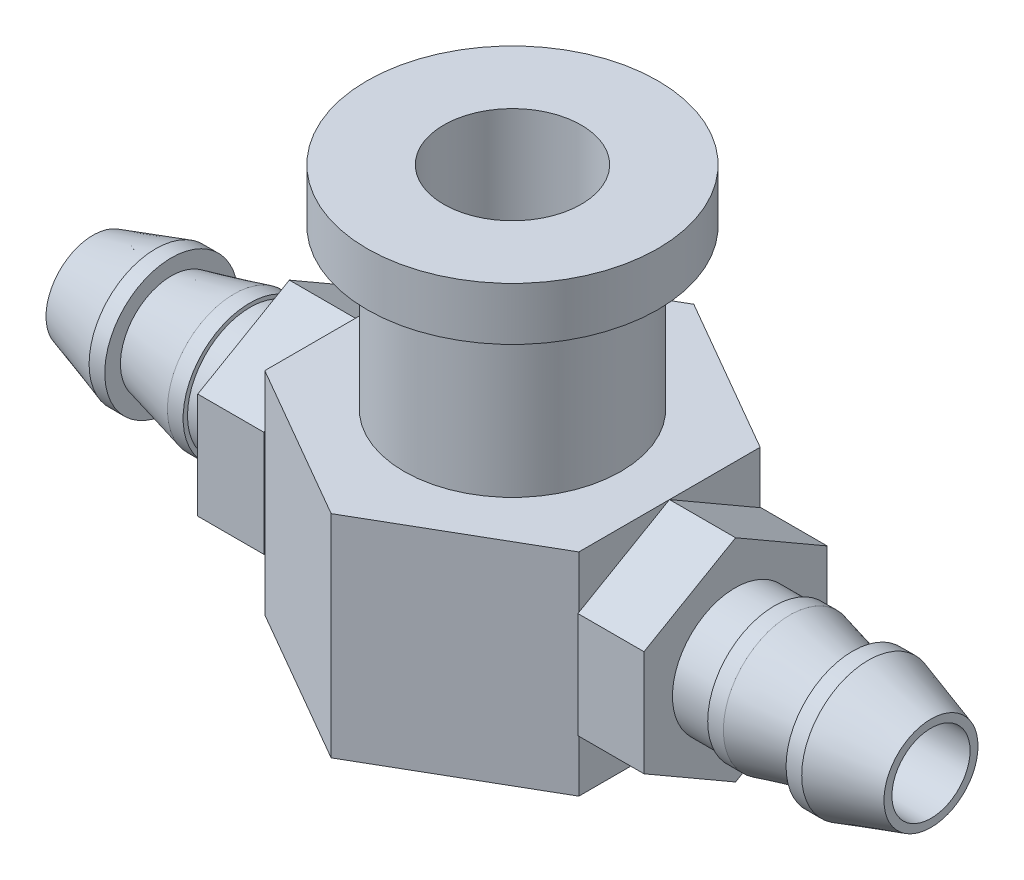
SolidWorks part; units mm, degrees
ref_plane "Front Plane" through (0, 0, 0) normal (0, 0, 1) x (1, 0, 0)
ref_plane "Top Plane" through (0, 0, 0) normal (0, 1, 0) x (1, 0, 0)
ref_plane "Right Plane" through (0, 0, 0) normal (1, 0, 0) x (0, 0, -1)
sketch "Sketch1" plane through (0, 0, 0) normal (0, 1, 0) x (1, 0, 0)
  circle A0 centre (0, 0) radius 4.1
  circle A1 centre (0, 0) radius 5.5
extrude "Boss-Extrude1" add sketch "Sketch1" along normal blind 2
sketch "Sketch2" plane through (0, 2, 0) normal (0, 1, 0) x (1, 0, 0)
  circle A0 centre (0, 0) radius 4.1
extrude "Boss-Extrude2" add sketch "Sketch2" against normal blind 8 separate body
sketch "Sketch4" plane through (0, 2, 0) normal (0, 1, 0) x (1, 0, 0)
  circle A0 centre (0, 0) radius 2.6
extrude "Boss-Extrude3" add sketch "Sketch4" against normal blind 22
sketch "Sketch5" plane through (0, -6, 0) normal (0, -1, 0) x (1, 0, 0)
  line L0 (0, 4.1) -> (0, 8.1972) construction
  line L1 (5.9385, -3.4286) -> (5.9385, 3.4286)
  line L2 (5.9385, 3.4286) -> (0, 6.8571)
  line L3 (0, 6.8571) -> (-5.9385, 3.4286)
  line L4 (-5.9385, 3.4286) -> (-5.9385, -3.4286)
  line L5 (-5.9385, -3.4286) -> (0, -6.8571)
  line L6 (0, -6.8571) -> (5.9385, -3.4286)
  line L7 (0, 4.1) -> (0, -9.45) construction
  circle A0 centre (0, 0) radius 5.9385 construction
  circle A1 centre (0, 0) radius 4.1 construction
  circle A2 centre (0, 0) radius 4.1 construction
  dimension "D1" = 13.7143
extrude "Boss-Extrude4" add sketch "Sketch5" along normal blind 8
sketch "Sketch6" plane through (5.9385, 0, 0) normal (1, 0, 0) x (0, 0, -1)
  line L0 (0, -6) -> (0, -14) construction
  line L1 (3.4286, -6) -> (-3.4286, -6) construction
  line L2 (3.4286, -14) -> (-3.4286, -14) construction
  line L4 (0, -14) -> (3.4641, -12)
  line L5 (3.4641, -12) -> (3.4641, -8)
  line L6 (3.4641, -8) -> (0, -6)
  line L7 (0, -6) -> (-3.4641, -8)
  line L8 (-3.4641, -8) -> (-3.4641, -12)
  line L9 (-3.4641, -12) -> (0, -14)
  circle A0 centre (0, -10) radius 3.4641 construction
extrude "Boss-Extrude5" add sketch "Sketch6" along normal blind 2.5
sketch "Sketch7" plane through (-5.9385, 0, 0) normal (-1, 0, 0) x (0, 0, 1)
  line L0 (0, -6) -> (0, -14) construction
  line L1 (3.4286, -6) -> (-3.4286, -6) construction
  line L2 (-2.6, -14) -> (2.6, -14) construction
  line L4 (0, -14) -> (3.4641, -12)
  line L5 (3.4641, -12) -> (3.4641, -8)
  line L6 (3.4641, -8) -> (0, -6)
  line L7 (0, -6) -> (-3.4641, -8)
  line L8 (-3.4641, -8) -> (-3.4641, -12)
  line L9 (-3.4641, -12) -> (0, -14)
  circle A0 centre (0, -10) radius 3.4641 construction
extrude "Boss-Extrude6" add sketch "Sketch7" along normal blind 2.5
sketch "Sketch8" plane through (0, 2, 0) normal (0, 1, 0) x (1, 0, 0)
  circle A0 centre (0, 0) radius 2.6
extrude "Cut-Extrude1" cut sketch "Sketch8" against normal up to surface (16 mm away) up to face at (0, -14, -2.6)
sketch "Sketch9" plane through (8.4385, 0, 0) normal (1, 0, 0) x (0, 0, -1)
  line L0 (-3.4641, -10) -> (3.4286, -10) construction
  line L1 (-3.4641, -8) -> (-3.4641, -12) construction
  line L2 (3.4286, -12.0205) -> (3.4286, -7.9795) construction
  circle A0 centre (-0.0178, -10) radius 2.3704
  dimension "D1" = 4.7407
extrude "Boss-Extrude7" add sketch "Sketch9" along normal blind 1.4815
sketch "Sketch10" plane through (-8.4385, 0, 0) normal (-1, 0, 0) x (0, 0, 1)
  line L0 (0, -6) -> (0, -14) construction
  circle A0 centre (0, -10) radius 2.3704
  dimension "D1" = 4.7407
extrude "Boss-Extrude8" add sketch "Sketch10" along normal blind 1.4815
sketch "Sketch11" plane through (9.9199, 0, 0) normal (1, 0, 0) x (0, 0, -1)
  circle A0 centre (-0.0178, -10) radius 2.5185
  dimension "D1" = 5.037
extrude "Boss-Extrude9" add sketch "Sketch11" along normal blind 0.5926
ref_plane "Plane1" through (12.8829, 0, 0) normal (1, 0, 0) x (0, 0, -1)
sketch "Sketch12" plane through (12.8829, 0, 0) normal (1, 0, 0) x (0, 0, -1)
  circle A0 centre (-0.0178, -10) radius 1.9259
  dimension "D1" = 3.8519
sketch "Sketch13" plane through (10.5125, 0, 0) normal (1, 0, 0) x (0, 0, -1)
  circle A0 centre (-0.0178, -10) radius 2.5185
loft "Loft1" add profiles "Sketch13", "Sketch12"
sketch "Sketch14" plane through (12.8829, 0, 0) normal (1, 0, 0) x (0, 0, -1)
  circle A0 centre (-0.0178, -10) radius 2.5185
extrude "Boss-Extrude10" add sketch "Sketch14" along normal blind 0.5926
ref_plane "Plane2" through (15.8459, 0, 0) normal (1, 0, 0) x (0, 0, -1)
sketch "Sketch15" plane through (15.8459, 0, 0) normal (1, 0, 0) x (0, 0, -1)
  circle A0 centre (-0.0178, -10) radius 1.7778
sketch "Sketch16" plane through (13.4755, 0, 0) normal (1, 0, 0) x (0, 0, -1)
  circle A0 centre (-0.0178, -10) radius 2.5185
loft "Loft2" add profiles "Sketch16", "Sketch15"
ref_plane "Plane3" through (0, 0, 0) normal (1, 0, 0) x (0, 0, -1)
mirror "Mirror1" about plane through (0, 0, 0) normal (1, 0, 0) of "Boss-Extrude10", "Loft2", "Loft1", "Boss-Extrude9"
sketch "Sketch17" plane through (15.8459, 0, 0) normal (1, 0, 0) x (0, 0, -1)
  circle A2 centre (-0.0178, -10) radius 1.4778
  circle A3 centre (-0.0178, -10) radius 1.4778
  dimension "D1" = 0.3
extrude "Cut-Extrude2" cut sketch "Sketch17" against normal up to surface (31.6917 mm away)
sketch "Sketch18" plane through (0, -20, 0) normal (0, -1, 0) x (1, 0, 0)
  circle A0 centre (0, 0) radius 2.6
extrude "Cut-Extrude3" cut sketch "Sketch18" against normal blind 6
sketch "Sketch21" plane through (0, -14, 0) normal (0, -1, 0) x (1, 0, 0)
  circle A0 centre (0, 0) radius 4
extrude "Cut-Extrude4" cut sketch "Sketch21" against normal blind 2
